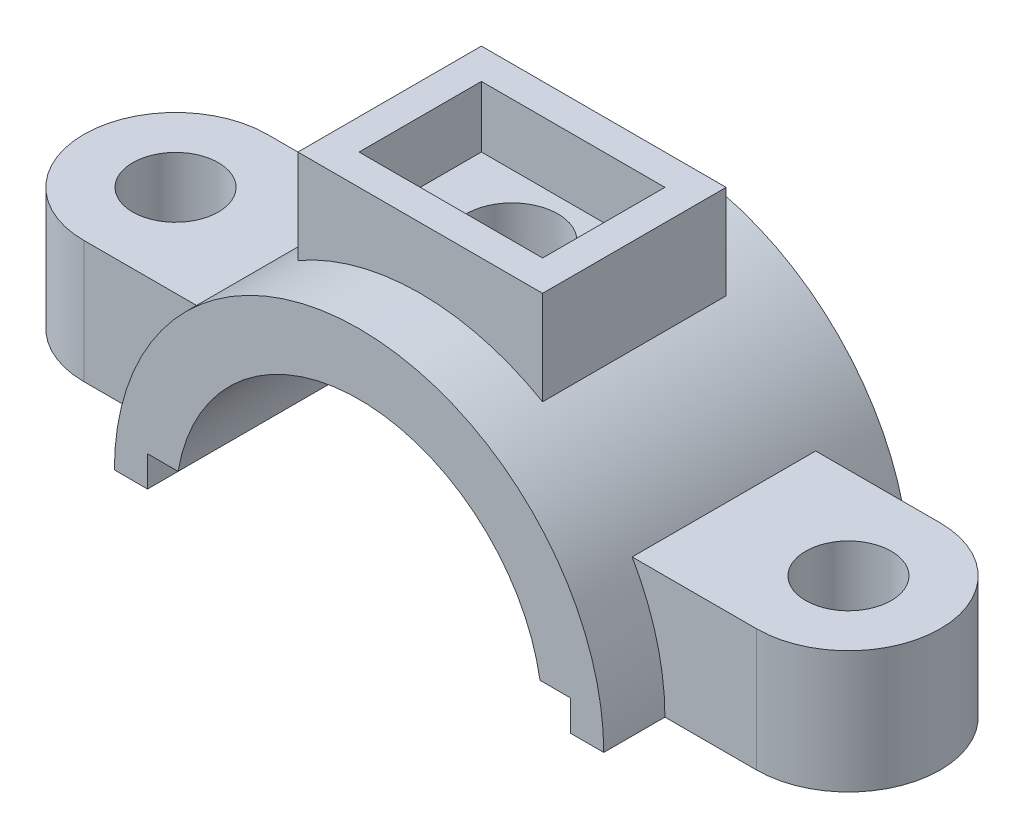
SolidWorks part; units mm, degrees
ref_plane "Front Plane" through (0, 0, 0) normal (0, 0, 1) x (1, 0, 0)
ref_plane "Top Plane" through (0, 0, 0) normal (0, 1, 0) x (1, 0, 0)
ref_plane "Right Plane" through (0, 0, 0) normal (1, 0, 0) x (0, 0, -1)
sketch "Sketch4" plane through (0, 0, 0) normal (0, 0, 1) x (1, 0, 0)
  line L0 (-40, 0) -> (40, 0) construction
  line L1 (-34.5804, 5) -> (-29.5804, 5)
  line L2 (-34.5804, 5) -> (-34.5804, 0)
  line L3 (-34.5804, 0) -> (-40, 0)
  line L4 (29.5804, 5) -> (34.5804, 5)
  line L5 (34.5804, 5) -> (34.5804, 0)
  line L6 (34.5804, 0) -> (40, 0)
  arc A0 (29.5804, 5) -> (-29.5804, 5) centre (0, 0) ccw
  arc A1 (40, 0) -> (-40, 0) centre (0, 0) ccw
  dimension "D1" = 60
  dimension "D2" = 80
  dimension "D3" = 5
  dimension "D4" = 5
extrude "Boss-Extrude3" add sketch "Sketch4" along normal mid plane 50
sketch "Sketch5" plane through (0, 0, 0) normal (0, 1, 0) x (1, 0, 0)
  line L0 (-55, 0) -> (55, 0) construction
  line L1 (-55, 15) -> (-34.5804, 15)
  line L2 (-55, -15) -> (-34.5804, -15)
  line L3 (-34.5804, 15) -> (-34.5804, -15)
  line L4 (0, 0) -> (0, 15) construction
  line L5 (34.5804, 15) -> (55, 15)
  line L6 (34.5804, 15) -> (34.5804, -15)
  line L7 (34.5804, -15) -> (55, -15)
  arc A0 (-55, 15) -> (-55, -15) centre (-55, 0) ccw
  arc A1 (55, -15) -> (55, 15) centre (55, 0) ccw
  circle A2 centre (-55, 0) radius 7
  circle A3 centre (55, 0) radius 7
  point P2 (0, 0)
  point P18 (-35.2594, -15.5173)
  point P19 (-32.8063, -15.2875)
  point P20 (0, 0)
  point P21 (0, 0)
  point P22 (0, 0)
  point P23 (0, 0)
  point P25 (0, 0)
  point P27 (0, 0)
  point P29 (0, 0)
  point P31 (0, 0)
  dimension "D2" = 15
  dimension "D3" = 14
  dimension "D1" = 110
extrude "Boss-Extrude4" add sketch "Sketch5" along normal blind 20
ref_plane "Plane2" through (0, 50, 0) normal (0, 1, 0) x (1, 0, 0)
sketch "Sketch8" plane through (0, 50, 0) normal (0, 1, 0) x (1, 0, 0)
  line L1 (-20, -15) -> (20, -15)
  line L2 (-20, -15) -> (-20, 15)
  line L3 (-20, 15) -> (20, 15)
  line L4 (20, -15) -> (20, 15)
  line L5 (-20, -15) -> (20, 15) construction
  line L6 (-20, 15) -> (20, -15) construction
  point P0 (0, 0)
  dimension "D1" = 40
  dimension "D2" = 30
extrude "Boss-Extrude6" add sketch "Sketch8" against normal up to surface (15.359 mm away)
sketch "Sketch9" plane through (0, 50, 0) normal (0, 1, 0) x (1, 0, 0)
  line L0 (-20, 15) -> (-20, -15) construction
  line L1 (15, -10) -> (-15, -10)
  line L2 (15, -10) -> (15, 10)
  line L3 (15, 10) -> (-15, 10)
  line L4 (-15, -10) -> (-15, 10)
  line L5 (15, -10) -> (-15, 10) construction
  line L6 (15, 10) -> (-15, -10) construction
  line L7 (20, 15) -> (-20, 15) construction
  point P0 (0, 0)
  dimension "D1" = 5
  dimension "D2" = 5
extrude "Cut-Extrude3" cut sketch "Sketch9" against normal blind 10
sketch "Sketch10" plane through (0, 50, 0) normal (0, 1, 0) x (1, 0, 0)
  circle A0 centre (0, 0) radius 7.5
  dimension "D1" = 15
extrude "Cut-Extrude4" cut sketch "Sketch10" against normal through all
